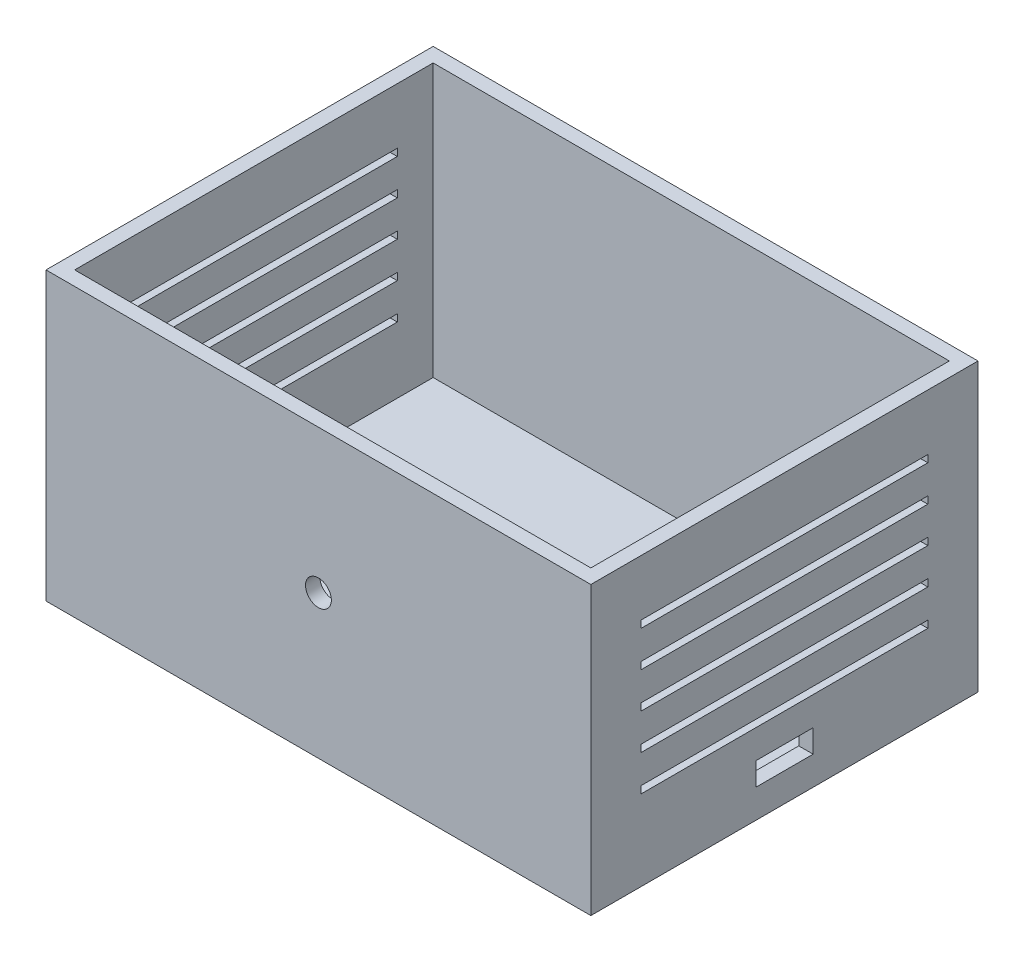
SolidWorks part; units mm, degrees
ref_plane "Front Plane" through (0, 0, 0) normal (0, 0, 1) x (1, 0, 0)
ref_plane "Top Plane" through (0, 0, 0) normal (0, 1, 0) x (1, 0, 0)
ref_plane "Right Plane" through (0, 0, 0) normal (1, 0, 0) x (0, 0, -1)
sketch "Sketch1" plane through (0, 0, 0) normal (0, 1, 0) x (1, 0, 0)
  line L0 (0, 0) -> (180, 0)
  line L1 (0, 0) -> (0, -125)
  line L2 (0, -125) -> (180, -125)
  line L3 (180, -125) -> (180, 0)
  line L4 (0, 0) -> (0, 5)
  line L5 (0, 5) -> (185, 5)
  line L6 (185, 5) -> (185, -130)
  line L7 (185, -130) -> (-5, -130)
  line L8 (-5, -130) -> (-5, 5)
  line L9 (-5, 5) -> (0, 5)
extrude "Boss-Extrude1" add sketch "Sketch1" along normal blind 100
sketch "Sketch2" plane through (0, 0, 0) normal (0, -1, 0) x (-1, 0, 0)
  line L0 (0, -125) -> (-180, -125)
  line L1 (-180, -125) -> (-180, 0)
  line L2 (-180, 0) -> (0, 0)
  line L3 (0, 0) -> (0, -125)
extrude "Boss-Extrude2" add sketch "Sketch2" against normal blind 5
sketch "Sketch3" plane through (185, 0, 0) normal (1, 0, 0) x (0, 0, -1)
  line L2 (-62.5, 10) -> (-52.5, 10)
  line L3 (-52.5, 10) -> (-52.5, 18)
  line L4 (-52.5, 18) -> (-72.5, 18)
  line L5 (-72.5, 18) -> (-72.5, 10)
  line L6 (-72.5, 10) -> (-62.5, 10)
  line L7 (-62.5, 28) -> (-12.5, 28)
  line L8 (-12.5, 28) -> (-12.5, 30.5)
  line L9 (-62.5, 28) -> (-112.5, 28)
  line L10 (-112.5, 28) -> (-112.5, 30.5)
  line L11 (-112.5, 30.5) -> (-12.5, 30.5)
  line L13 (-12.5, 40.5) -> (-112.5, 40.5)
  line L14 (-112.5, 40.5) -> (-112.5, 43)
  line L15 (-112.5, 43) -> (-12.5, 43)
  line L16 (-12.5, 43) -> (-12.5, 40.5)
  line L18 (-12.5, 53) -> (-112.5, 53)
  line L19 (-112.5, 53) -> (-112.5, 55.5)
  line L20 (-112.5, 55.5) -> (-12.5, 55.5)
  line L21 (-12.5, 55.5) -> (-12.5, 53)
  line L23 (-12.5, 65.5) -> (-112.5, 65.5)
  line L24 (-112.5, 65.5) -> (-112.5, 68)
  line L25 (-112.5, 68) -> (-12.5, 68)
  line L26 (-12.5, 68) -> (-12.5, 65.5)
  line L28 (-12.5, 78) -> (-112.5, 78)
  line L29 (-112.5, 78) -> (-112.5, 80.5)
  line L30 (-112.5, 80.5) -> (-12.5, 80.5)
  line L31 (-12.5, 80.5) -> (-12.5, 78)
extrude "Cut-Extrude1" cut sketch "Sketch3" against normal blind 200
sketch "Sketch4" plane through (-5, 0, 0) normal (-1, 0, 0) x (0, 0, 1)
  line L0 (52.5, 18) -> (72.5, 18)
  line L1 (72.5, 18) -> (72.5, 10)
  line L2 (72.5, 10) -> (52.5, 10)
  line L3 (52.5, 10) -> (52.5, 18)
extrude "Boss-Extrude4" add sketch "Sketch4" against normal blind 5
sketch "Sketch5" plane through (0, 0, 130) normal (0, 0, 1) x (1, 0, 0)
  line L0 (90, 0) -> (90, 50)
  line L1 (185, 0) -> (-5, 0) construction
  circle A0 centre (90, 50) radius 4.5
extrude "Cut-Extrude2" cut sketch "Sketch5" against normal blind 5
